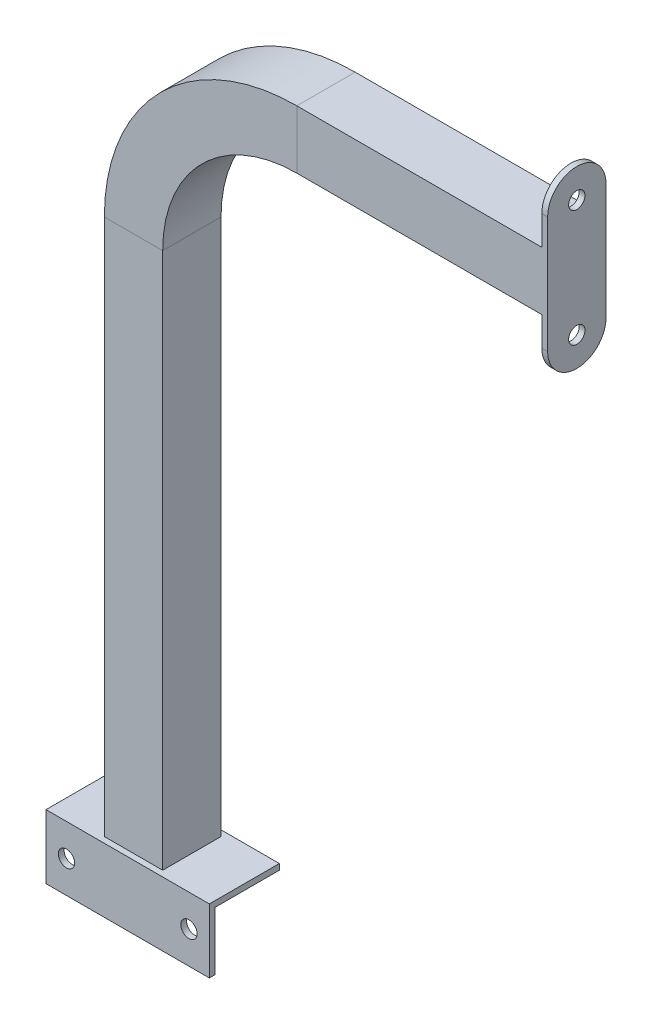
SolidWorks part; units mm, degrees
ref_plane "Front Plane" through (0, 0, 0) normal (0, 0, 1) x (1, 0, 0)
ref_plane "Top Plane" through (0, 0, 0) normal (0, 1, 0) x (1, 0, 0)
ref_plane "Right Plane" through (0, 0, 0) normal (1, 0, 0) x (0, 0, -1)
sketch "Sketch2" plane through (0, 0, 0) normal (0, 1, 0) x (1, 0, 0)
  line L0 (-1000, 0) -> (49000, 0) construction
  line L2 (70, 30) -> (-70, 30)
  line L3 (70, -30) -> (70, 30)
  line L4 (-70, -30) -> (-70, 30)
  line L5 (70, -30) -> (-70, -30)
  point P4 (0, 0)
  point P14 (0, 30)
extrude "Boss-Extrude2" add sketch "Sketch2" against normal blind 5
sketch "Sketch3" plane through (0, -5, 0) normal (0, -1, 0) x (1, 0, 0)
  line L0 (70, -30) -> (-70, -30) construction
  line L1 (-70, 30) -> (70, 30) construction
  line L2 (70, -30) -> (-70, -30)
  line L3 (-70, 30) -> (70, 30)
  line L4 (-70, 25) -> (70, 25)
  line L5 (2.75, 0) -> (-2.75, 0) construction
  line L6 (-70, -25) -> (70, -25)
  line L7 (-70, 30) -> (-70, 25)
  line L8 (70, 30) -> (70, 25)
  line L9 (-70, -25) -> (-70, -30)
  line L10 (70, -25) -> (70, -30)
extrude "Boss-Extrude3" add sketch "Sketch3" along normal blind 50
sketch "Sketch4" plane through (0, 0, -30) normal (0, 0, -1) x (-1, 0, 0)
  line L0 (0, -1000) -> (0, 49000) construction
  line L1 (-70, 0) -> (70, 0) construction
  line L2 (-930, -27.5) -> (49070, -27.5) construction
  line L3 (70, -55) -> (70, 0) construction
  line L4 (52.5, -27.5) -> (-52.5, -27.5) construction
  circle A0 centre (-52.5, -27.5) radius 7
  circle A1 centre (52.5, -27.5) radius 7
  point P5 (0, 0)
  point P10 (70, -27.5)
  point P13 (0, -27.5)
  dimension "D1" = 14
extrude "Cut-Extrude1" cut sketch "Sketch4" against normal through all
sketch "Sketch5" plane through (0, 0, 0) normal (0, 0, 1) x (1, 0, 0)
  line L0 (0, 0) -> (0, 460)
  line L1 (0, 460) -> (140, 460) construction
  line L2 (140, 600) -> (350, 600)
  arc A0 (140, 600) -> (0, 460) centre (140, 460) ccw
  point P0 (0, 0)
  dimension "D3" = 600
  dimension "D1" = 140
  dimension "D2" = 350
sketch "Sketch6" plane through (0, 0, 0) normal (0, 1, 0) x (1, 0, 0)
  line L0 (20, 20) -> (-20, 20)
  line L1 (25, -25) -> (-25, -25)
  line L2 (25, -25) -> (25, 25)
  line L3 (25, 25) -> (-25, 25)
  line L4 (-25, -25) -> (-25, 25)
  line L5 (25, -25) -> (-25, 25) construction
  line L6 (25, 25) -> (-25, -25) construction
  line L7 (-20, -20) -> (-20, 20)
  line L8 (20, -20) -> (-20, -20)
  line L9 (20, -20) -> (20, 20)
  point P0 (0, 0)
  point P2 (0, 0)
  dimension "D1" = 50
  dimension "D2" = 50
sweep "Sweep1" add profiles "Sketch6" path "Sketch5"
sketch "Sketch7" plane through (350, 0, 0) normal (1, 0, 0) x (0, 0, -1)
  line L0 (0, 625) -> (0, 575) construction
  line L1 (25, 625) -> (-25, 625) construction
  line L2 (0, 600) -> (0, 460) construction
  line L3 (25, 600) -> (-25, 600) construction
  line L4 (25, 575) -> (25, 625) construction
  line L5 (-25, 625) -> (-25, 575) construction
  line L6 (0, 550) -> (0, 650) construction
  line L7 (-25, 550) -> (-25, 650)
  line L8 (25, 550) -> (25, 650)
  arc A0 (25, 650) -> (-25, 650) centre (0, 650) ccw
  circle A1 centre (0, 650) radius 7
  circle A2 centre (0, 550) radius 7
  arc A3 (25, 550) -> (-25, 550) centre (0, 550) cw
  point P16 (0, 600)
  dimension "D1" = 50
  dimension "D2" = 14
extrude "Boss-Extrude4" add sketch "Sketch7" along normal blind 5
sketch "Sketch8" plane through (0, 0, -30) normal (0, 0, -1) x (-1, 0, 0)
  line L1 (-70, -55) -> (70, -55)
  line L2 (-70, -55) -> (-70, -5)
  line L3 (-70, -5) -> (70, -5)
  line L4 (70, -55) -> (70, -5)
extrude "Cut-Extrude2" cut sketch "Sketch8" against normal up to surface (5 mm away) up to face at (45.5, -27.5, -25)
